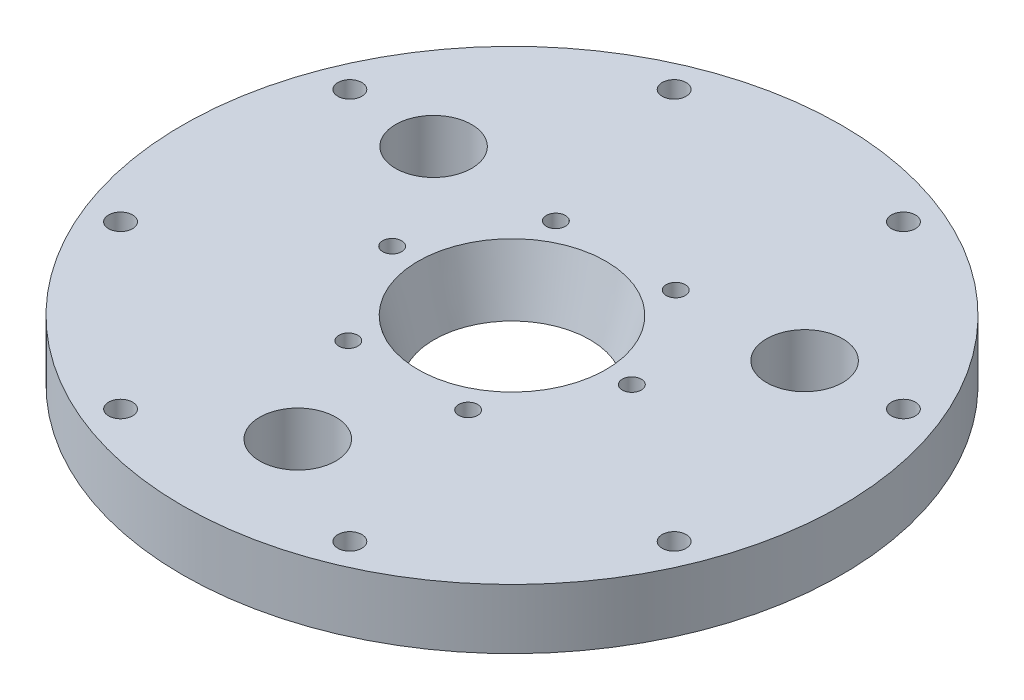
SolidWorks part; units mm, degrees
material "AISI 1020"
ref_plane "Front Plane" through (0, 0, 0) normal (0, 0, 1) x (1, 0, 0)
ref_plane "Top Plane" through (0, 0, 0) normal (0, 1, 0) x (1, 0, 0)
ref_plane "Right Plane" through (0, 0, 0) normal (1, 0, 0) x (0, 0, -1)
sketch "Sketch1" plane through (0, 0, 0) normal (0, 1, 0) x (1, 0, 0)
  circle A0 centre (0, 0) radius 55
  dimension "D1" = 110
extrude "Boss-Extrude1" add sketch "Sketch1" along normal blind 10 contours A0
sketch "Sketch5" plane through (0, 0, 0) normal (0, 0, 1) x (1, 0, 0)
  line L0 (0, 0) -> (0, 29.9809) construction
  line L1 (0, 0) -> (0, 10)
  line L2 (13, 0) -> (15.6795, 10)
  line L4 (55, 10) -> (-55, 10) construction
  line L6 (-55, 0) -> (55, 0) construction
  line L7 (0, 0) -> (13, 0)
  line L8 (15.6795, 10) -> (0, 10)
  line L9 (13, 0) -> (13, 10) construction
  dimension "D1" = 13
  dimension "D3" = 15
revolve "Cut-Revolve1" cut sketch "Sketch5" angle 360 about L0
sketch "Sketch6" plane through (0, 0, 0) normal (0, 1, 0) x (1, 0, 0)
  line L0 (0, 0) -> (46.194, 19.1342) construction
  line L1 (0, 0) -> (55, 0) construction
  circle A0 centre (46.194, 19.1342) radius 2
  circle A1 centre (0, 0) radius 55 construction
  dimension "D1" = 4
  dimension "D2" = 50
  dimension "D3" = 22.5
extrude "Cut-Extrude3" cut sketch "Sketch6" along normal through all
pattern_circular "CirPattern1" count 8 over 360 about axis through (0, 0, 0) along (0, 1, 0) of "Cut-Extrude3"
sketch "Sketch7" plane through (0, 10, 0) normal (0, 1, 0) x (1, 0, 0)
  line L0 (0, 0) -> (30.9604, 17.875) construction
  line L1 (0, 0) -> (54.5383, 0) construction
  circle A0 centre (30.9604, 17.875) radius 6.35
  dimension "D1" = 12.7
  dimension "D2" = 35.75
  dimension "D3" = 30
extrude "Cut-Extrude4" cut sketch "Sketch7" against normal through all
pattern_circular "CirPattern2" count 3 over 360 about axis through (0, 0, 0) along (0, 1, 0) of "Cut-Extrude4"
sketch "Sketch8" plane through (0, 10, 0) normal (0, 1, 0) x (1, 0, 0)
  line L0 (0, 0) -> (20, 0) construction
  circle A0 centre (20, 0) radius 1.5875
  dimension "D2" = 3.175
  dimension "D1" = 20
extrude "Cut-Extrude5" cut sketch "Sketch8" against normal blind 7
pattern_circular "CirPattern3" count 6 over 360 about axis through (0, 0, 0) along (0, 1, 0) of "Cut-Extrude5"
